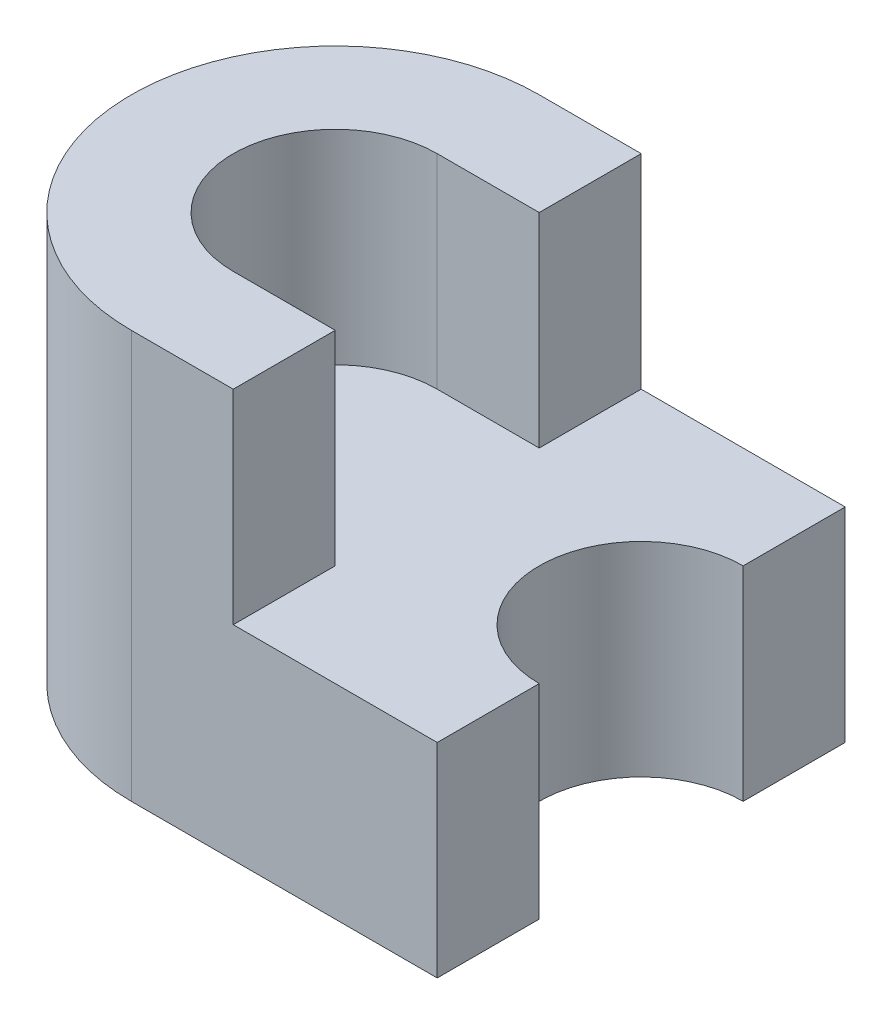
SolidWorks part; units mm, degrees
ref_plane "Front Plane" through (0, 0, 0) normal (0, 0, 1) x (1, 0, 0)
ref_plane "Top Plane" through (0, 0, 0) normal (0, 1, 0) x (1, 0, 0)
ref_plane "Right Plane" through (0, 0, 0) normal (1, 0, 0) x (0, 0, -1)
sketch "Sketch1" plane through (0, 0, 0) normal (0, 1, 0) x (1, 0, 0)
  line L0 (0, 20) -> (30, 20)
  line L1 (30, 20) -> (30, 10)
  line L2 (30, -20) -> (0, -20)
  line L3 (30, -10) -> (30, -20)
  arc A0 (0, 20) -> (0, -20) centre (0, 0) ccw
  arc A1 (30, 10) -> (30, -10) centre (30, 0) ccw
  dimension "D1" = 40
  dimension "D2" = 30
  dimension "D3" = 30
extrude "Boss-Extrude1" add sketch "Sketch1" along normal blind 20
sketch "Sketch2" plane through (0, 20, 0) normal (0, 1, 0) x (1, 0, 0)
  line L0 (0, 20) -> (10, 20)
  line L1 (30, 20) -> (0, 20) construction
  line L2 (10, 20) -> (10, 10)
  line L3 (0, -20) -> (30, -20) construction
  line L4 (10, -20) -> (0, -20)
  line L5 (0, 10) -> (10, 10)
  line L6 (0, -10) -> (10, -10)
  line L7 (10, -10) -> (10, -20)
  arc A0 (0, 20) -> (0, -20) centre (0, 0) ccw
  arc A1 (0, 10) -> (0, -10) centre (0, 0) ccw
  point P3 (0, 0)
  dimension "D2" = 20
  dimension "D3" = 10
extrude "Boss-Extrude2" add sketch "Sketch2" along normal blind 20 contours A1 L6 L7 L4 A0 L0 L2 L5
